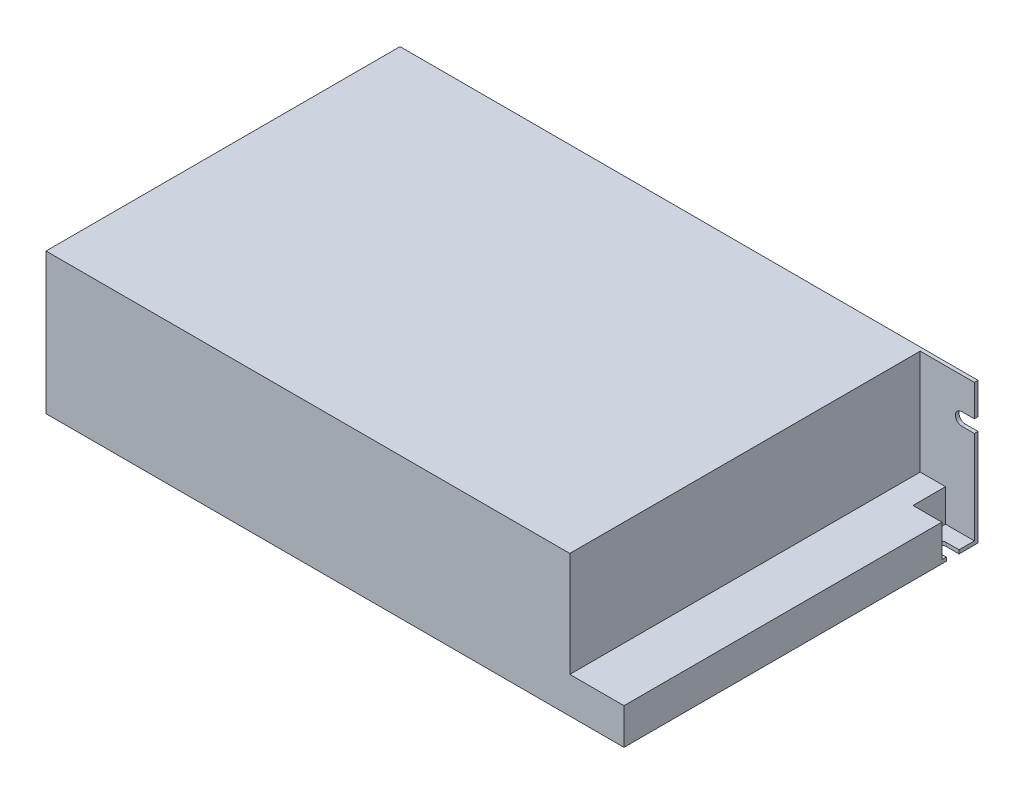
SolidWorks part; units mm, degrees
ref_plane "前视基准面" through (0, 0, 0) normal (0, 0, 1) x (1, 0, 0)
ref_plane "上视基准面" through (0, 0, 0) normal (0, 1, 0) x (1, 0, 0)
ref_plane "右视基准面" through (0, 0, 0) normal (1, 0, 0) x (0, 0, -1)
sketch "草图1" plane through (0, 0, 0) normal (0, 1, 0) x (1, 0, 0)
  line L0 (0, 55.5934) -> (0, -59.528) construction
  line L1 (-86.9906, 0) -> (86.3218, 0) construction
  line L3 (-80, 49) -> (80, 49)
  line L4 (-80, 49) -> (-80, -49)
  line L5 (-80, -49) -> (80, -49)
  line L6 (80, 49) -> (80, -49)
  dimension "D1" = 160
  dimension "D2" = 98
extrude "拉伸1" add sketch "草图1" along normal blind 39
sketch "草图2" plane through (80, 0, 0) normal (1, 0, 0) x (0, 0, -1)
  line L0 (49, 39) -> (49, 0) construction
  line L1 (-49, 39) -> (48, 39)
  line L2 (-49, 39) -> (-49, 10)
  line L3 (-49, 10) -> (48, 10)
  line L4 (48, 39) -> (48, 10)
  line L5 (-49, 0) -> (49, 0) construction
  dimension "D1" = 1
  dimension "D2" = 10
extrude "切除-拉伸1" cut sketch "草图2" against normal blind 15
sketch "草图3" plane through (0, 0, -49) normal (0, 0, -1) x (-1, 0, 0)
  line L0 (80, 39) -> (80, 0) construction
  line L1 (-86.7646, 28.5) -> (88.9626, 28.5) construction
  line L2 (-80, 0) -> (80, 0) construction
  line L3 (-76.5, 30.25) -> (-80, 30.25)
  line L4 (-59, -10.8443) -> (-59, 41.6068) construction
  line L5 (-80, 39) -> (-80, 0) construction
  line L6 (-76.5, 26.75) -> (-80, 26.75)
  line L7 (-80, 30.25) -> (-80, 26.75)
  circle A0 centre (-59, 28.5) radius 1.75
  circle A1 centre (73.5, 28.5) radius 1.75
  circle A2 centre (58, 19) radius 1.75
  circle A3 centre (-59, 10.5) radius 1.75
  arc A4 (-76.5, 26.75) -> (-76.5, 30.25) centre (-76.5, 28.5) ccw
  dimension "D1" = 3.5
  dimension "D3" = 3.5
  dimension "D8" = 3.5
  dimension "D10" = 3.5
  dimension "D11" = 3.5
  dimension "D2" = 22
  dimension "D4" = 28.5
  dimension "D5" = 6.5
  dimension "D6" = 19
  dimension "D7" = 117
  dimension "D9" = 18
  dimension "D12" = 150
extrude "切除-拉伸2" cut sketch "草图3" against normal blind 5
sketch "草图4" plane through (0, 0, 0) normal (0, -1, 0) x (1, 0, 0)
  line L0 (-63.448, -16) -> (30.6569, -16) construction
  line L1 (22, -21.9255) -> (22, 28.1345) construction
  line L2 (28.9106, 16) -> (-61.3354, 16) construction
  line L3 (-56, -31.821) -> (-56, 29.2986) construction
  line L4 (-80, -49) -> (-80, 49) construction
  line L5 (80, -49) -> (-80, -49) construction
  line L6 (76.5, -43.75) -> (80, -43.75)
  line L7 (80, 49) -> (80, -48) construction
  line L8 (76.5, -40.25) -> (80, -40.25)
  line L9 (80, -43.75) -> (80, -40.25)
  circle A0 centre (22, -16) radius 1.75
  circle A1 centre (22, 16) radius 1.75
  circle A2 centre (-56, -16) radius 1.75
  circle A3 centre (-56, 16) radius 1.75
  circle A5 centre (-75.5, 43.5) radius 1.75
  arc A6 (76.5, -40.25) -> (76.5, -43.75) centre (76.5, -42) ccw
  dimension "D5" = 3.5
  dimension "D6" = 3.5
  dimension "D7" = 3.5
  dimension "D8" = 3.5
  dimension "D9" = 3.5
  dimension "D10" = 3.5
  dimension "D1" = 32
  dimension "D2" = 78
  dimension "D3" = 24
  dimension "D4" = 33
  dimension "D11" = 4.5
  dimension "D12" = 152
  dimension "D13" = 85.5
  dimension "D14" = 7
extrude "切除-拉伸3" cut sketch "草图4" against normal blind 5
sketch "草图5" plane through (0, 10, 0) normal (0, 1, 0) x (-1, 0, 0)
  line L1 (-80, -48) -> (-72, -48)
  line L2 (-80, -48) -> (-80, -39)
  line L3 (-80, -39) -> (-72, -39)
  line L4 (-72, -48) -> (-72, -39)
  dimension "D1" = 8
  dimension "D2" = 9
extrude "切除-拉伸4" cut sketch "草图5" against normal offset from surface (9 mm away) 1 up to face at (-75.5, 0, 41.75)
